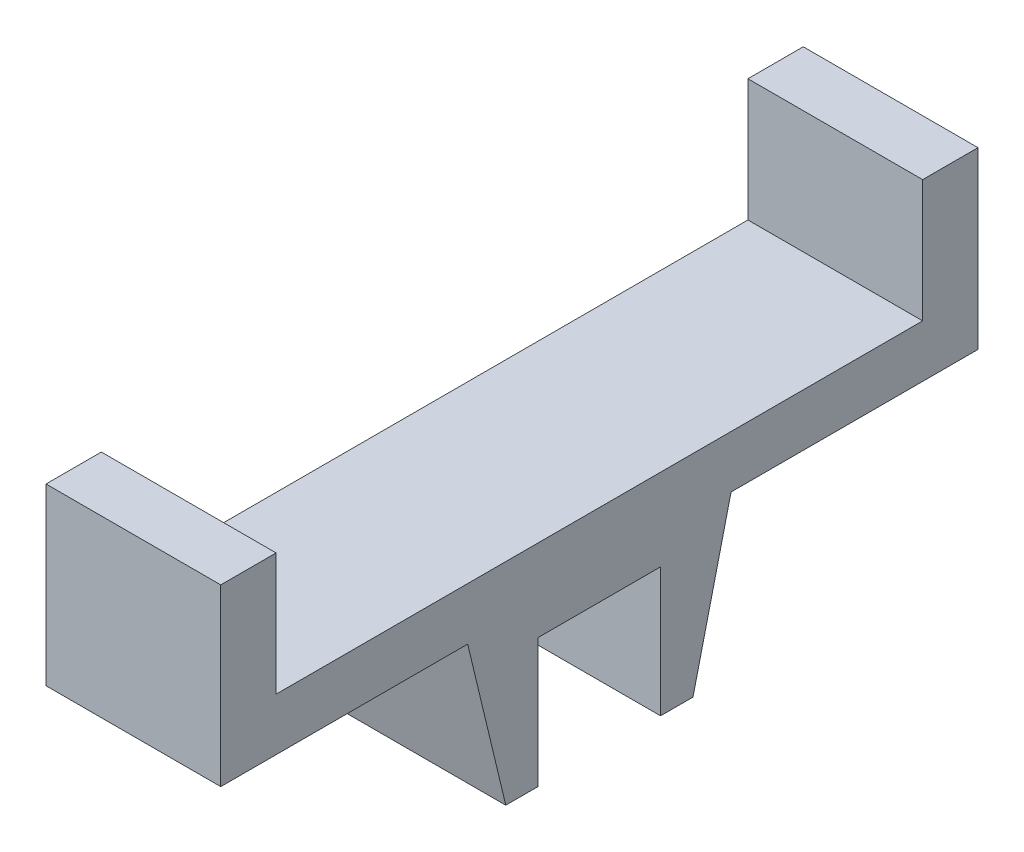
SolidWorks part; units mm, degrees
ref_plane "前视基准面" through (0, 0, 0) normal (0, 0, 1) x (1, 0, 0)
ref_plane "上视基准面" through (0, 0, 0) normal (0, 1, 0) x (1, 0, 0)
ref_plane "右视基准面" through (0, 0, 0) normal (1, 0, 0) x (0, 0, -1)
sketch "草图2" plane through (0, 0, 0) normal (0, 1, 0) x (1, 0, 0)
  line L0 (10.5472, 61.1118) -> (10.5472, -3.8882)
  line L1 (10.5472, -3.8882) -> (25.5472, -3.8882)
  line L2 (25.5472, -3.8882) -> (25.5472, 61.1118)
  line L3 (25.5472, 61.1118) -> (10.5472, 61.1118)
  dimension "D1" = 15
  dimension "D2" = 65
extrude "凸台-拉伸1" add sketch "草图2" along normal blind 15
sketch "草图7" plane through (10.5472, 0, 0) normal (-1, 0, 0) x (0, 0, 1)
  line L0 (-56.3618, 15) -> (-56.3618, 4.5)
  line L1 (-61.1118, 15) -> (3.8882, 15) construction
  line L2 (-56.3618, 4.5) -> (-0.8618, 4.5)
  line L3 (-0.8618, 4.5) -> (-0.8618, 15)
  line L4 (-0.8618, 15) -> (-56.3618, 15)
  line L6 (-61.1118, 15) -> (-61.1118, 0) construction
  line L7 (-61.1118, 0) -> (3.8882, 0) construction
  dimension "D1" = 55.5
  dimension "D2" = 4.75
  dimension "D3" = 4.5
extrude "切除-拉伸3" cut sketch "草图7" against normal through all
sketch "草图8" plane through (10.5472, 0, 0) normal (-1, 0, 0) x (0, 0, 1)
  line L1 (-61.1118, 0) -> (3.8882, 0) construction
  line L2 (-17.3068, 0) -> (-20.5768, -13.6127)
  line L6 (3.8882, 15) -> (3.8882, 0) construction
  line L9 (-33.8618, -2.5374) -> (-23.3618, -2.5374)
  line L10 (-23.3618, -2.5374) -> (-23.3618, -13.6127)
  line L12 (-23.3618, -13.6127) -> (-20.5768, -13.6127)
  line L14 (-39.9168, 0) -> (-36.6468, -13.6127)
  line L15 (-33.8618, -13.6127) -> (-36.6468, -13.6127)
  line L16 (-33.8618, -2.5374) -> (-33.8618, -13.6127)
  line L17 (-39.9168, 0) -> (-17.3068, 0)
  point P17 (-28.6118, -2.5374)
  dimension "D1" = 21.195
  dimension "D2" = 2.785
  dimension "D4" = 14
  dimension "D6" = 5.25
extrude "凸台-拉伸3" add sketch "草图8" against normal blind 15
